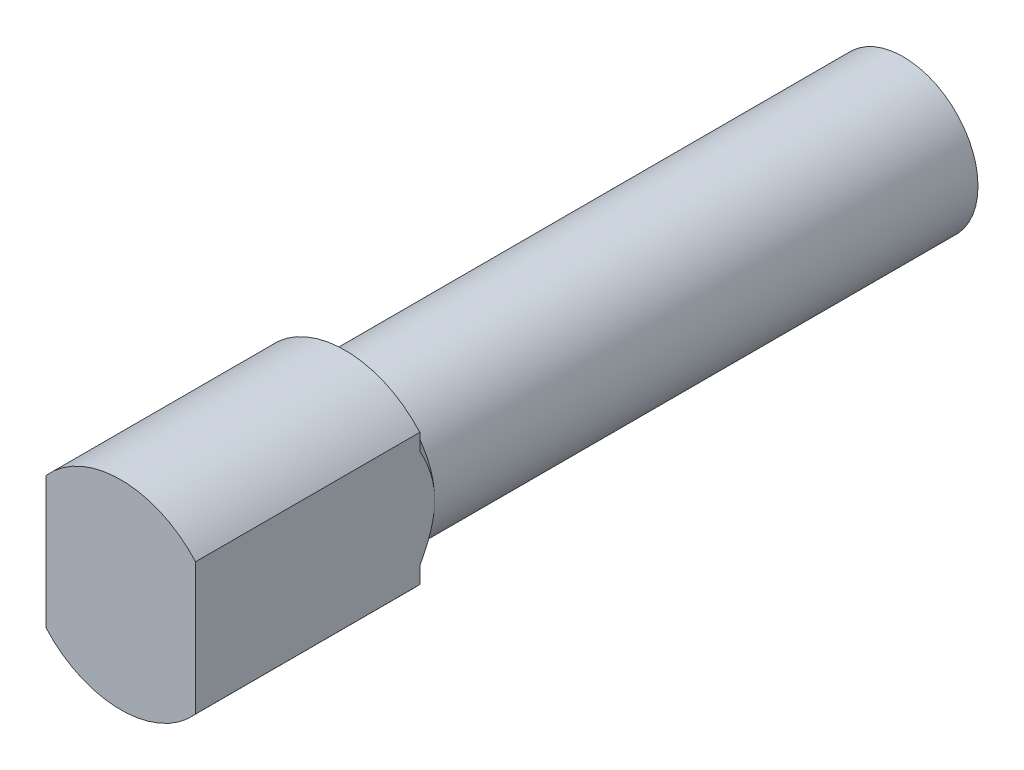
SolidWorks part; units mm, degrees
ref_plane "Спереди" through (0, 0, 0) normal (0, 0, 1) x (1, 0, 0)
ref_plane "Сверху" through (0, 0, 0) normal (0, 1, 0) x (1, 0, 0)
ref_plane "Справа" through (0, 0, 0) normal (1, 0, 0) x (0, 0, -1)
sketch "Эскиз1" plane through (0, 0, 0) normal (0, 0, 1) x (1, 0, 0)
  circle A0 centre (0, 0) radius 15
extrude "Вытянуть1" add sketch "Эскиз1" along normal blind 112
sketch "Эскиз2" plane through (0, 0, 112) normal (0, 0, 1) x (1, 0, 0)
  circle A0 centre (0, 0) radius 20
extrude "Вытянуть2" add sketch "Эскиз2" along normal blind 45
chamfer "Фаска1" distance 3 angle 45 1 edges at (15, 0, 112)
sketch "Эскиз3" plane through (0, 0, 157) normal (0, 0, 1) x (1, 0, 0)
  line L0 (0, 0) -> (0, 21.677) construction
  line L1 (30.4529, -21.3014) -> (15, -21.3014)
  line L2 (-30.4529, 20.7649) -> (-15, 20.7649)
  line L3 (-30.4529, 20.7649) -> (-30.4529, -21.3014)
  line L4 (-30.4529, -21.3014) -> (-15, -21.3014)
  line L5 (-15, 20.7649) -> (-15, -21.3014)
  line L6 (30.4529, 20.7649) -> (30.4529, -21.3014)
  line L7 (15, 20.7649) -> (15, -21.3014)
  line L8 (30.4529, 20.7649) -> (15, 20.7649)
  dimension "D1" = 15
extrude "Вытянуть3" cut sketch "Эскиз3" against normal through all
